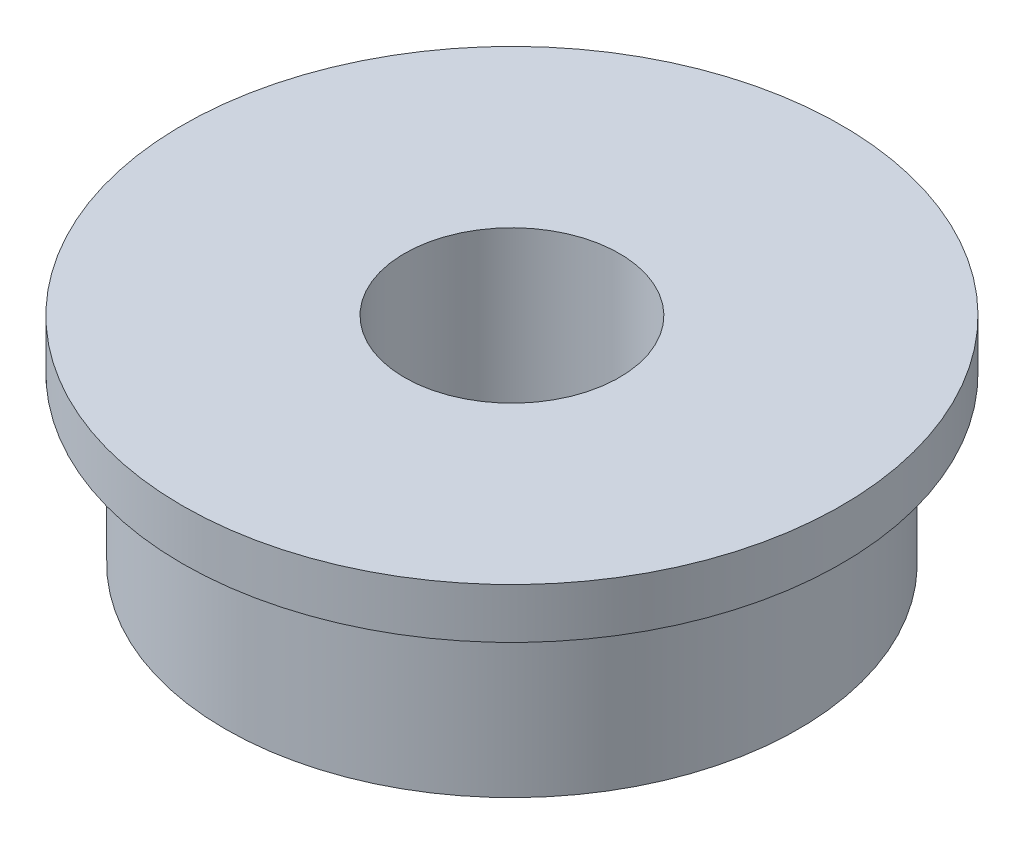
SolidWorks part; units mm, degrees
ref_plane "前视基准面" through (0, 0, 0) normal (0, 0, 1) x (1, 0, 0)
ref_plane "上视基准面" through (0, 0, 0) normal (0, 1, 0) x (1, 0, 0)
ref_plane "右视基准面" through (0, 0, 0) normal (1, 0, 0) x (0, 0, -1)
sketch "草图2" plane through (0, 0, 0) normal (0, 0, 1) x (1, 0, 0)
  line L0 (0, 8.3242) -> (0, -8.6646) construction
  line L1 (1.5, 6.9421) -> (4.6, 6.9421)
  line L2 (4.6, 6.9421) -> (4.6, 6.2421)
  line L3 (4.6, 6.2421) -> (4, 6.2421)
  line L4 (4, 6.2421) -> (4, 3.9421)
  line L5 (4, 3.9421) -> (1.5, 3.9421)
  line L6 (1.5, 6.9421) -> (1.5, 3.9421)
  point P3 (4.6, 6.5921)
  dimension "D1" = 3
  dimension "D2" = 1.5
  dimension "D3" = 4
  dimension "D4" = 0.7
  dimension "D5" = 4.6
revolve "旋转1" add sketch "草图2" angle 360 about L0
